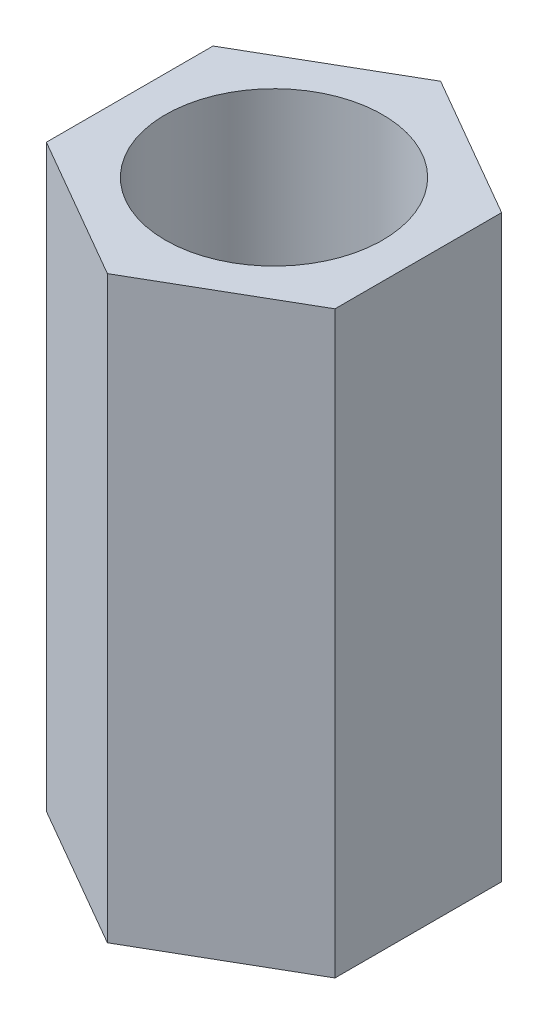
SolidWorks part; units mm, degrees
material "黄铜"
ref_plane "前视基准面" through (0, 0, 0) normal (0, 0, 1) x (1, 0, 0)
ref_plane "上视基准面" through (0, 0, 0) normal (0, 1, 0) x (1, 0, 0)
ref_plane "右视基准面" through (0, 0, 0) normal (1, 0, 0) x (0, 0, -1)
other "Configuration Table"
sketch "草图1" plane through (0, 0, 0) normal (0, 1, 0) x (1, 0, 0)
  line L0 (0, 0) -> (0, 3.0947) construction
  line L1 (1.9919, 1.15) -> (0, 2.3)
  line L2 (0, 2.3) -> (-1.9919, 1.15)
  line L3 (-1.9919, 1.15) -> (-1.9919, -1.15)
  line L4 (-1.9919, -1.15) -> (0, -2.3)
  line L5 (0, -2.3) -> (1.9919, -1.15)
  line L6 (1.9919, -1.15) -> (1.9919, 1.15)
  circle A0 centre (0, 0) radius 1.5
  circle A1 centre (0, 0) radius 1.9919 construction
  dimension "D1" = 3
  dimension "D2" = 4.6
extrude "凸台-拉伸1" add sketch "草图1" along normal blind 8
